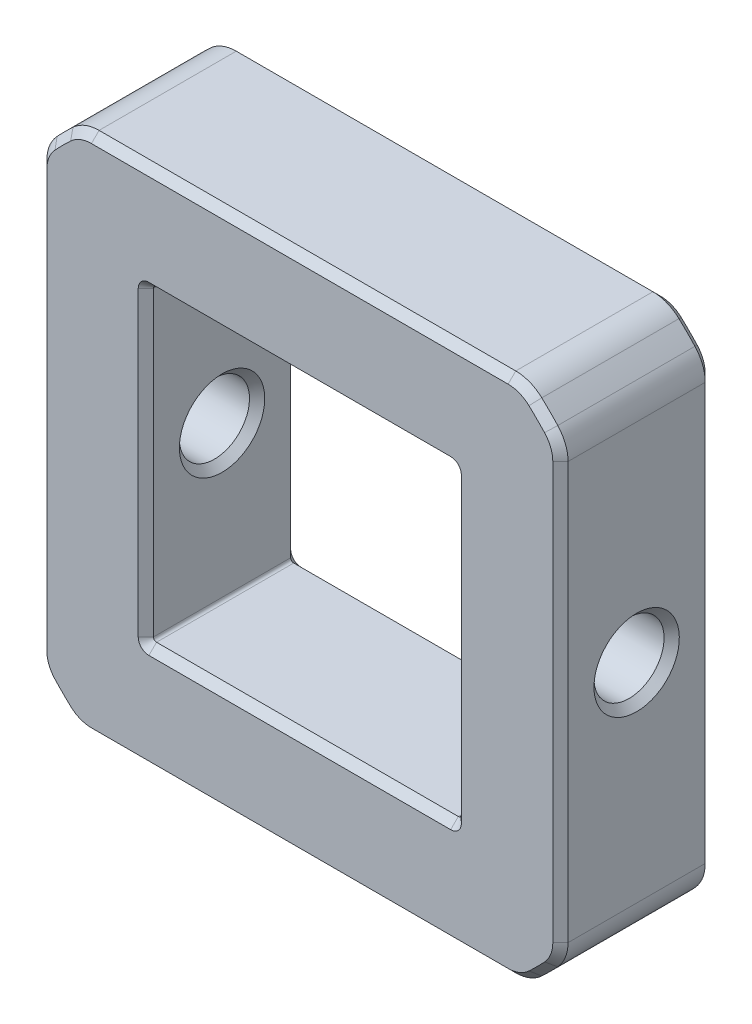
SolidWorks part; units mm, degrees
ref_plane "Front" through (0, 0, 0) normal (0, 0, 1) x (1, 0, 0)
ref_plane "Top" through (0, 0, 0) normal (0, 1, 0) x (1, 0, 0)
ref_plane "Right" through (0, 0, 0) normal (1, 0, 0) x (0, 0, -1)
sketch "Skizze1" plane through (0, 0, 0) normal (0, 0, 1) x (1, 0, 0)
  line L0 (14.6233, 17.1) -> (-14.6233, 17.1)
  line L1 (-10.1, -10.1) -> (10.1, -10.1)
  line L2 (-10.1, -10.1) -> (-10.1, 10.1)
  line L3 (-10.1, 10.1) -> (10.1, 10.1)
  line L4 (10.1, -10.1) -> (10.1, 10.1)
  line L5 (-10.1, -10.1) -> (10.1, 10.1) construction
  line L6 (-10.1, 10.1) -> (10.1, -10.1) construction
  line L7 (17.1, 14.6233) -> (17.1, -14.6233)
  line L8 (-14.6233, -17.1) -> (14.6233, -17.1)
  line L9 (-17.1, -14.6233) -> (-17.1, 14.6233)
  arc A0 (-17.1, -14.6233) -> (-14.6233, -17.1) centre (0, 0) ccw
  arc A1 (-14.6233, 17.1) -> (-17.1, 14.6233) centre (0, 0) ccw
  arc A2 (17.1, 14.6233) -> (14.6233, 17.1) centre (0, 0) ccw
  arc A3 (14.6233, -17.1) -> (17.1, -14.6233) centre (0, 0) ccw
  dimension "D1" = 45
  dimension "D2" = 20.2
  dimension "D3" = 7
extrude "Aufsatz-Linear austragen1" add sketch "Skizze1" along normal blind 10
fillet "Verrundung1" radius 0.2 4 edges at (10.1, -10.1, 5) (-10.1, -10.1, 5) (-10.1, 10.1, 5) (10.1, 10.1, 5)
fillet "Verrundung2" radius 2.5 8 edges at (14.6233, 17.1, 5) (17.1, 14.6233, 5) (17.1, -14.6233, 5) (14.6233, -17.1, 5) (-14.6233, -17.1, 5) (-17.1, -14.6233, 5) (-17.1, 14.6233, 5) (-14.6233, 17.1, 5)
sketch "Skizze2" plane through (17.1, 0, 0) normal (1, 0, 0) x (0, 0, -1)
  line L0 (0, 0) -> (-10, 0) construction
  line L1 (-10, -13.6689) -> (-10, 13.6689) construction
  circle A0 centre (-5, 0) radius 2.3
  dimension "D1" = 4.6
extrude "Schnitt-Linear austragen1" cut sketch "Skizze2" against normal through all
chamfer "Fase2" distance 0.5 angle 45 52 edges at (17.1, 2.3, 5) (10.1, 0, 7.3) (-17.1, 2.3, 5) (-10.1, 0, 2.7) (-10.0414, 10.0414, 10) (-10.1, 0, 10) (-10.0414, -10.0414, 10) (0, -10.1, 10) (10.0414, -10.0414, 10) (10.1, 0, 10) (10.0414, 10.0414, 10) (0, 10.1, 10) (16.9251, 14.5875, 10) (17.1, 0, 10) (16.9251, -14.5875, 10) (15.9099, -15.9099, 10) (14.5875, -16.9251, 10) (0, -17.1, 10) (-14.5875, -16.9251, 10) (-15.9099, -15.9099, 10) (-16.9251, -14.5875, 10) (-17.1, 0, 10) (-16.9251, 14.5875, 10) (-15.9099, 15.9099, 10) (-14.5875, 16.9251, 10) (0, 17.1, 10) (14.5875, 16.9251, 10) (15.9099, 15.9099, 10) (-10.0414, -10.0414, 0) (-10.1, 0, 0) (-10.0414, 10.0414, 0) (0, 10.1, 0) (10.0414, 10.0414, 0) (10.1, 0, 0) (10.0414, -10.0414, 0) (0, -10.1, 0) (-14.5875, 16.9251, 0) (-15.9099, 15.9099, 0) (-16.9251, 14.5875, 0) (-17.1, 0, 0) (-16.9251, -14.5875, 0) (-15.9099, -15.9099, 0) (-14.5875, -16.9251, 0) (0, -17.1, 0) (14.5875, -16.9251, 0) (15.9099, -15.9099, 0) (16.9251, -14.5875, 0) (17.1, 0, 0) (16.9251, 14.5875, 0) (15.9099, 15.9099, 0) (14.5875, 16.9251, 0) (0, 17.1, 0)
